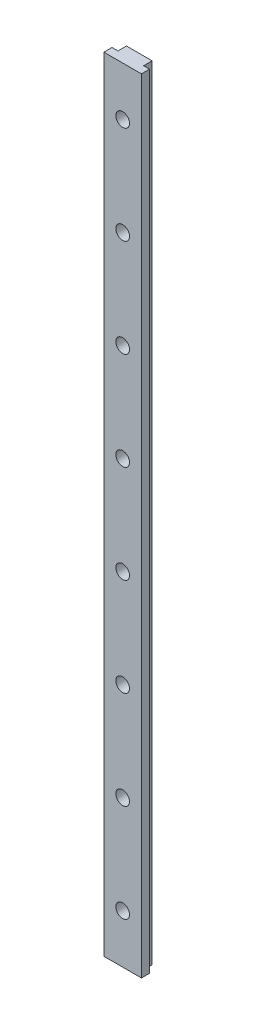
SolidWorks part; units mm, degrees
ref_plane "Front Plane" through (0, 0, 0) normal (0, 0, 1) x (1, 0, 0)
ref_plane "Top Plane" through (0, 0, 0) normal (0, 1, 0) x (1, 0, 0)
ref_plane "Right Plane" through (0, 0, 0) normal (1, 0, 0) x (0, 0, -1)
sketch "Sketch1" plane through (0, 0, 0) normal (0, 1, 0) x (1, 0, 0)
  line L0 (0, 0) -> (0, 3.5072) construction
  line L1 (-2.4384, 0) -> (2.4384, 0)
  line L2 (-2.4384, 0) -> (-2.4384, 1.0541)
  line L3 (-2.4384, 1.0541) -> (2.4384, 1.0541)
  line L4 (2.4384, 0) -> (2.4384, 1.0541)
  line L5 (-1.6637, 1.0541) -> (1.6637, 1.0541)
  line L6 (-1.6637, 1.0541) -> (-1.6637, 2.159)
  line L7 (-1.6637, 2.159) -> (1.6637, 2.159)
  line L8 (1.6637, 1.0541) -> (1.6637, 2.159)
  point P11 (0, 0)
  point P12 (0, 0)
  dimension "D1" = 4.8768
  dimension "D2" = 3.3274
  dimension "D3" = 1.0541
  dimension "D4" = 2.159
extrude "Boss-Extrude1" add sketch "Sketch1" along normal blind 101.6 contours L3 L0 L7 L6 | L0 L5 L8 L7 | L0 L1 L4 L3 L5 | L1 L0 L3 L2
sketch "Sketch2" plane through (0, 0, -2.159) normal (0, 0, -1) x (-1, 0, 0)
  line L0 (0, 101.6) -> (0, 0) construction
  line L1 (1.6637, 101.6) -> (-1.6637, 101.6) construction
  circle A0 centre (0, 6.35) radius 0.889
  circle A1 centre (0, 19.05) radius 0.889
  circle A2 centre (0, 31.75) radius 0.889
  circle A3 centre (0, 44.45) radius 0.889
  circle A4 centre (0, 57.15) radius 0.889
  circle A5 centre (0, 69.85) radius 0.889
  circle A6 centre (0, 82.55) radius 0.889
  circle A7 centre (0, 95.25) radius 0.889
  dimension "D1" = 1.778
  dimension "D2" = 6.35
  dimension "D3" = 8
extrude "Cut-Extrude1" cut sketch "Sketch2" against normal up to next
